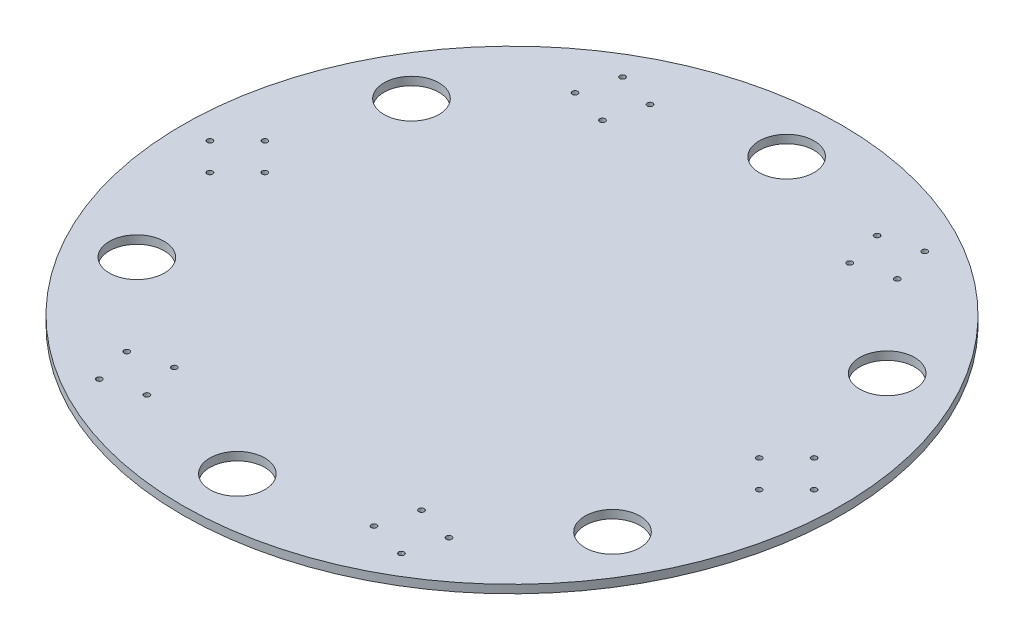
SolidWorks part; units mm, degrees
material "Acrylic (Medium-high impact)"
ref_plane "Front Plane" through (0, 0, 0) normal (0, 0, 1) x (1, 0, 0)
ref_plane "Top Plane" through (0, 0, 0) normal (0, 1, 0) x (1, 0, 0)
ref_plane "Right Plane" through (0, 0, 0) normal (1, 0, 0) x (0, 0, -1)
sketch "Sketch1" plane through (0, 0, 0) normal (0, 1, 0) x (1, 0, 0)
  circle A0 centre (0, 0) radius 120
  circle A1 centre (0, 0) radius 100 construction
  circle A2 centre (100, 0) radius 10 construction
  circle A3 centre (45, -77.9423) radius 1
  circle A4 centre (58.6603, -81.6025) radius 1
  circle A5 centre (55, -95.2628) radius 1
  circle A6 centre (50, -86.6025) radius 10 construction
  circle A7 centre (41.3397, -91.6025) radius 1
  circle A8 centre (110, 0) radius 1
  circle A9 centre (100, -10) radius 1
  circle A10 centre (100, 0) radius 10 construction
  circle A11 centre (90, 0) radius 1
  circle A12 centre (100, 0) radius 10 construction
  circle A13 centre (100, 10) radius 1
  circle A14 centre (100, 0) radius 10 construction
  circle A15 centre (-45, -77.9423) radius 1
  circle A16 centre (-41.3397, -91.6025) radius 1
  circle A17 centre (-55, -95.2628) radius 1
  circle A18 centre (-50, -86.6025) radius 10 construction
  circle A19 centre (-58.6603, -81.6025) radius 1
  circle A20 centre (-90, 0) radius 1
  circle A21 centre (-100, -10) radius 1
  circle A22 centre (-110, 0) radius 1
  circle A23 centre (-100, 0) radius 10 construction
  circle A24 centre (-100, 10) radius 1
  circle A25 centre (-45, 77.9423) radius 1
  circle A26 centre (-58.6603, 81.6025) radius 1
  circle A27 centre (-55, 95.2628) radius 1
  circle A28 centre (-50, 86.6025) radius 10 construction
  circle A29 centre (-41.3397, 91.6025) radius 1
  circle A30 centre (45, 77.9423) radius 1
  circle A31 centre (41.3397, 91.6025) radius 1
  circle A32 centre (55, 95.2628) radius 1
  circle A33 centre (50, 86.6025) radius 10 construction
  circle A34 centre (58.6603, 81.6025) radius 1
  circle A35 centre (0, 100) radius 10
  circle A36 centre (-86.6025, 50) radius 10
  circle A37 centre (-86.6025, -50) radius 10
  circle A38 centre (0, -100) radius 10
  circle A39 centre (86.6025, -50) radius 10
  circle A40 centre (86.6025, 50) radius 10
  point P19 (0, 0)
  point P31 (100, 0)
  point P71 (0, 0)
  point P85 (0, 0)
  dimension "D1" = 6
  dimension "D2" = 4
  dimension "D3" = 240
  dimension "D4" = 200
  dimension "D5" = 20
  dimension "D6" = 2
  dimension "D7" = 100
  dimension "D8" = 200
  dimension "D9" = 20
  dimension "D10" = 6
extrude "Boss-Extrude1" add sketch "Sketch1" along normal blind 3
sketch3d "3DSketch1"
  circle A0 centre (-110, 3, 0) radius 1 construction
  circle A1 centre (110, 3, 0) radius 1 construction
  circle A2 centre (55, 3, -95.2628) radius 1 construction
  circle A3 centre (-55, 3, 95.2628) radius 1 construction
  circle A4 centre (-55, 3, -95.2628) radius 1 construction
  circle A5 centre (55, 3, 95.2628) radius 1 construction
  point P2 (-110, 4, 0)
  point P5 (110, 4, 0)
  point P8 (55, 4, -95.2628)
  point P11 (-55, 4, 95.2628)
  point P14 (-55, 4, -95.2628)
  point P17 (55, 4, 95.2628)
